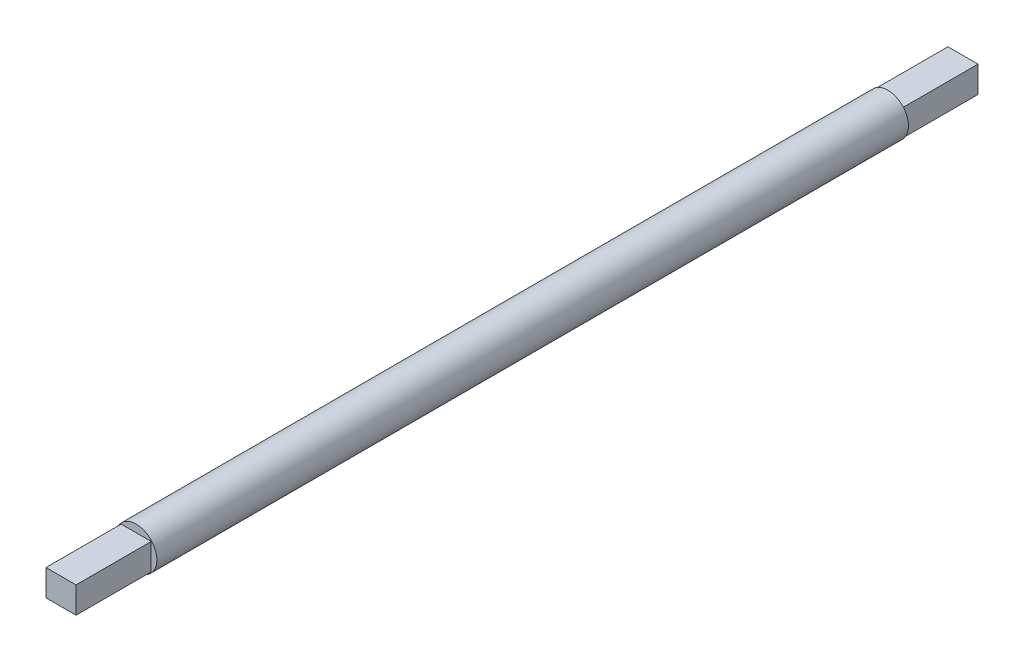
SolidWorks part; units mm, degrees
ref_plane "Front Plane" through (0, 0, 0) normal (0, 0, 1) x (1, 0, 0)
ref_plane "Top Plane" through (0, 0, 0) normal (0, 1, 0) x (1, 0, 0)
ref_plane "Right Plane" through (0, 0, 0) normal (1, 0, 0) x (0, 0, -1)
sketch "Sketch1" plane through (0, 0, 0) normal (0, 0, 1) x (1, 0, 0)
  circle A0 centre (0, 0) radius 2.75
  point P10 (0.0989, -0.0025)
  dimension "D1" = 5.5
extrude "Boss-Extrude1" add sketch "Sketch1" along normal blind 100
sketch "Sketch3" plane through (0, 0, 100) normal (0, 0, 1) x (1, 0, 0)
  line L1 (-2, 1.75) -> (2, 1.75)
  line L2 (-2, 1.75) -> (-2, -1.75)
  line L3 (-2, -1.75) -> (2, -1.75)
  line L4 (2, 1.75) -> (2, -1.75)
  dimension "D1" = 4
  dimension "D2" = 1.75
  dimension "D3" = 3.5
  dimension "D4" = 2
extrude "Boss-Extrude2" add sketch "Sketch3" along normal blind 10
sketch "Sketch4" plane through (0, 0, 0) normal (0, 0, -1) x (-1, 0, 0)
  line L1 (-2, 1.75) -> (2, 1.75)
  line L2 (-2, 1.75) -> (-2, -1.75)
  line L3 (-2, -1.75) -> (2, -1.75)
  line L4 (2, 1.75) -> (2, -1.75)
  dimension "D1" = 4
  dimension "D2" = 3.5
  dimension "D3" = 1.75
  dimension "D4" = 2
extrude "Boss-Extrude3" add sketch "Sketch4" along normal blind 10
